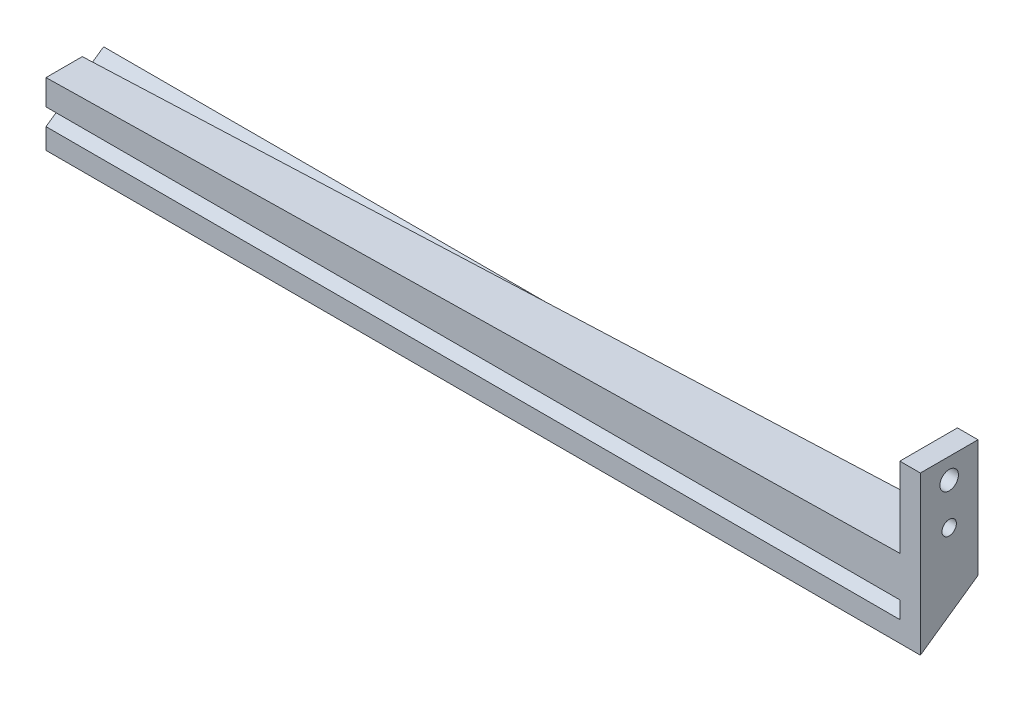
SolidWorks part; units mm, degrees
ref_plane "前视基准面" through (0, 0, 0) normal (0, 0, 1) x (1, 0, 0)
ref_plane "上视基准面" through (0, 0, 0) normal (0, 1, 0) x (1, 0, 0)
ref_plane "右视基准面" through (0, 0, 0) normal (1, 0, 0) x (0, 0, -1)
other "Configuration Table"
sketch "草图1" plane through (0, 0, 0) normal (1, 0, 0) x (0, 0, -1)
  line L0 (-31.0095, 41.3553) -> (-3.0095, 41.3553)
  line L1 (-3.0095, 41.3553) -> (-3.0095, -15.7447)
  line L2 (-3.0095, -15.7447) -> (-31.0095, -35.3505)
  line L3 (-31.0095, -35.3505) -> (-31.0095, 41.3553)
  dimension "D1" = 125
  dimension "D2" = 28
  dimension "D3" = 57.1
extrude "凸台-拉伸1" add sketch "草图1" along normal blind 425
sketch "草图2" plane through (0, 0, 31.0095) normal (0, 0, 1) x (1, 0, 0)
  line L0 (425, 41.3553) -> (0, 41.3553) construction
  line L1 (425, 41.3553) -> (425, -35.3505) construction
  line L2 (415, 41.3553) -> (415, 2.5553)
  line L3 (415, 2.5553) -> (0, -4.6886)
  line L4 (0, 41.3553) -> (0, -35.3505) construction
  line L5 (415, 41.3553) -> (0, 41.3553)
  line L6 (0, 41.3553) -> (0, -4.6886)
  point P0 (415, 41.3553)
  dimension "D1" = 10
  dimension "D2" = 38.8
  dimension "D3" = 91
extrude "切除-拉伸1" cut sketch "草图2" against normal blind 425
sketch "草图4" plane through (425, 0, 0) normal (1, 0, 0) x (0, 0, -1)
  line L0 (-31.0095, 41.3553) -> (-31.0095, -35.3505) construction
  line L1 (-3.0095, 41.3553) -> (-31.0095, 41.3553) construction
  circle A0 centre (-17.0095, 31.3553) radius 4.5
  circle A2 centre (-17.0095, 11.3553) radius 3.5
  dimension "D3" = 9
  dimension "D4" = 20
  dimension "D5" = 7
  dimension "D1" = 14
  dimension "D2" = 10
extrude "切除-拉伸2" cut sketch "草图4" against normal blind 425
sketch "草图6" plane through (425, 0, 0) normal (1, 0, 0) x (0, 0, -1)
  line L0 (-31.0095, -25.3402) -> (-3.0095, -5.7344)
  line L1 (-31.0095, 41.3553) -> (-31.0095, -35.3505) construction
  line L2 (-3.0095, -15.7447) -> (-3.0095, 41.3553) construction
  line L3 (-31.0095, -17.0389) -> (-3.0095, 2.5669)
  line L4 (-31.0095, -35.3505) -> (-3.0095, -15.7447) construction
  line L5 (-31.0095, -17.0389) -> (-31.0095, -25.3402)
  line L6 (-3.0095, 2.5669) -> (-3.0095, -5.7344)
  dimension "D3" = 8.2
  dimension "D4" = 15
extrude "切除-拉伸3" cut sketch "草图6" against normal up to next (425 mm away) from surface at -10 starting at face at (415, 31.3553, 12.5095)
